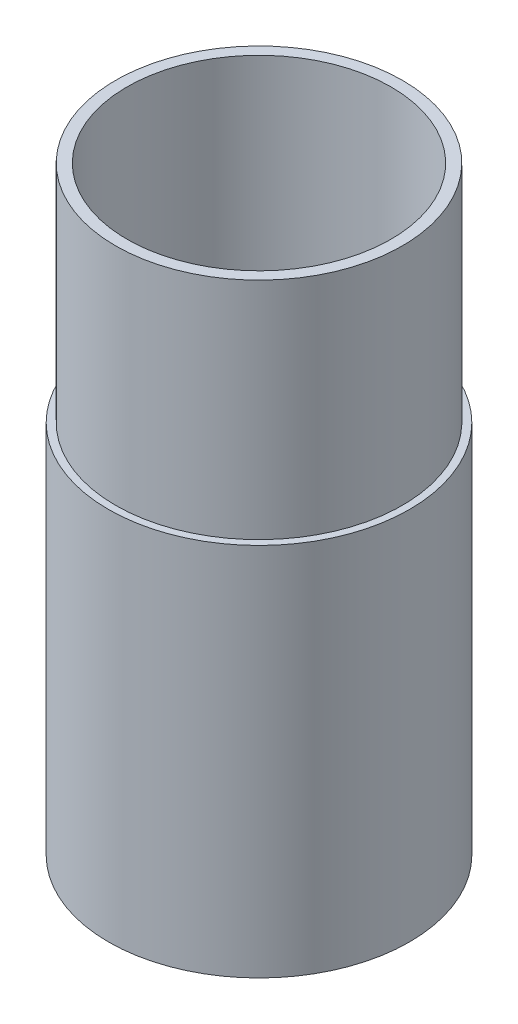
SolidWorks part; units mm, degrees
material "E-Glass Fiber"
ref_plane "Front Plane" through (0, 0, 0) normal (0, 0, 1) x (1, 0, 0)
ref_plane "Top Plane" through (0, 0, 0) normal (0, 1, 0) x (1, 0, 0)
ref_plane "Right Plane" through (0, 0, 0) normal (1, 0, 0) x (0, 0, -1)
sketch "Sketch1" plane through (0, 0, 0) normal (0, 0, 1) x (1, 0, 0)
  line L0 (0, 0) -> (0, 49.7577) construction
  line L1 (22.3799, -43.5737) -> (24.3103, -43.5737)
  line L2 (22.3799, -43.5737) -> (22.3799, 58.0263)
  line L3 (22.3799, 58.0263) -> (24.3103, 58.0263)
  line L4 (24.3103, -43.5737) -> (24.3103, 58.0263)
  line L5 (24.3103, -43.5737) -> (25.5143, -43.5737)
  line L6 (24.3103, -43.5737) -> (24.3103, 19.9263)
  line L7 (24.3103, 19.9263) -> (25.5143, 19.9263)
  line L8 (25.5143, -43.5737) -> (25.5143, 19.9263)
  line L9 (25.5143, -729.3737) -> (25.5143, 19.9263) construction
  point P10 (22.3799, 77.2018)
  point P12 (24.3103, 77.2018)
  point P14 (22.3799, -24.3982)
  point P16 (25.5143, -24.3982)
  point P18 (25.5143, 19.9263)
  point P21 (25.5143, 19.9263)
revolve "Revolve1" add sketch "Sketch1" angle 360 about L0
